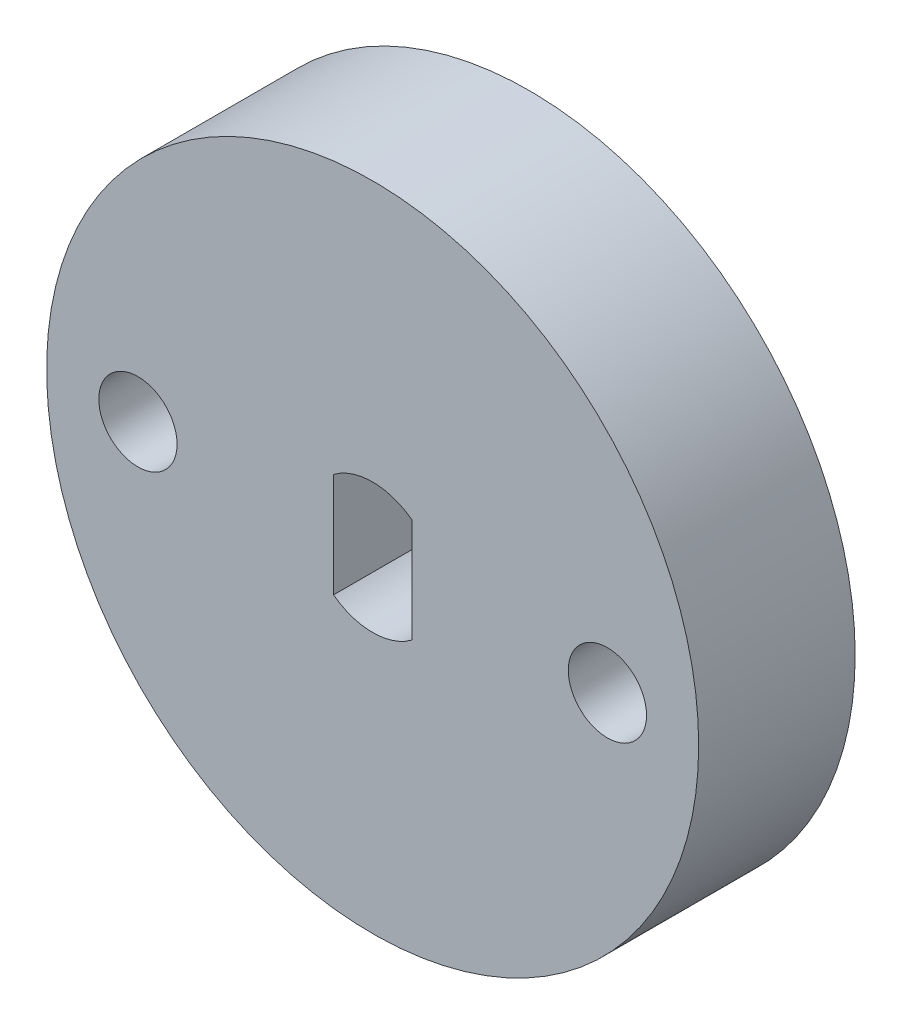
SolidWorks part; units mm, degrees
ref_plane "Front Plane" through (0, 0, 0) normal (0, 0, 1) x (1, 0, 0)
ref_plane "Top Plane" through (0, 0, 0) normal (0, 1, 0) x (1, 0, 0)
ref_plane "Right Plane" through (0, 0, 0) normal (1, 0, 0) x (0, 0, -1)
sketch "Sketch1" plane through (0, 0, 0) normal (0, 0, 1) x (1, 0, 0)
  circle A0 centre (0, 0) radius 12.5
  dimension "D1" = 25
extrude "Boss-Extrude1" add sketch "Sketch1" along normal mid plane 6
sketch "Sketch2" plane through (0, 0, 3) normal (0, 0, 1) x (1, 0, 0)
  line L0 (9, 0) -> (-9, 0) construction
  line L3 (1.5, -2) -> (1.5, 2)
  line L5 (-1.5, -2) -> (-1.5, 2)
  line L6 (1.5, -2) -> (-1.5, 2) construction
  line L7 (1.5, 2) -> (-1.5, -2) construction
  circle A0 centre (-9, 0) radius 1.5
  circle A1 centre (9, 0) radius 1.5
  arc A2 (1.5, 2) -> (-1.5, 2) centre (0, 0) ccw
  arc A3 (-1.5, -2) -> (1.5, -2) centre (0, 0) ccw
  point P4 (0, 0)
  dimension "D2" = 3
  dimension "D3" = 5
  dimension "D1" = 18
  dimension "D4" = 3
extrude "Cut-Extrude1" cut sketch "Sketch2" against normal through all
